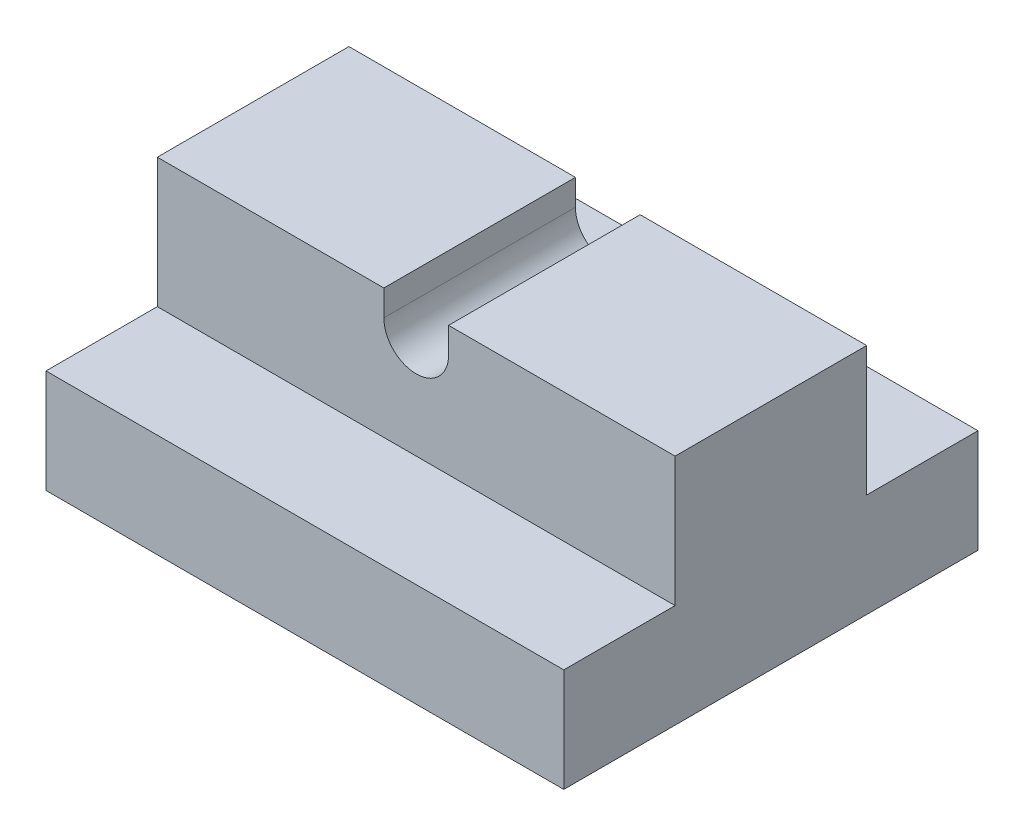
SolidWorks part; units mm, degrees
ref_plane "Front Plane" through (0, 0, 0) normal (0, 0, 1) x (1, 0, 0)
ref_plane "Top Plane" through (0, 0, 0) normal (0, 1, 0) x (1, 0, 0)
ref_plane "Right Plane" through (0, 0, 0) normal (1, 0, 0) x (0, 0, -1)
sketch "Sketch1" plane through (0, 0, 0) normal (0, 1, 0) x (1, 0, 0)
  line L1 (-5, -4) -> (5, -4)
  line L2 (-5, -4) -> (-5, 4)
  line L3 (-5, 4) -> (5, 4)
  line L4 (5, -4) -> (5, 4)
  line L5 (-5, -4) -> (5, 4) construction
  line L6 (-5, 4) -> (5, -4) construction
  point P0 (0, 0)
  dimension "D1" = 10
  dimension "D2" = 8
extrude "Boss-Extrude1" add sketch "Sketch1" along normal blind 2
sketch "Sketch2" plane through (0, 2, 0) normal (0, 1, 0) x (1, 0, 0)
  line L6 (5, -4) -> (5, 4) construction
  line L7 (-5, -1.85) -> (5, -1.85)
  line L8 (-5, -1.85) -> (-5, 1.85)
  line L9 (-5, 1.85) -> (5, 1.85)
  line L10 (5, -1.85) -> (5, 1.85)
  line L11 (-5, -1.85) -> (5, 1.85) construction
  line L12 (-5, 1.85) -> (5, -1.85) construction
  point P0 (0, 0)
  dimension "D1" = 3.7
extrude "Boss-Extrude2" add sketch "Sketch2" along normal blind 2.5
sketch "Sketch3" plane through (0, 0, 1.85) normal (0, 0, 1) x (1, 0, 0)
  line L0 (-5, 2) -> (5, 2) construction
  line L1 (-0.625, 4) -> (-0.625, 4.5)
  line L2 (-5, 4.5) -> (5, 4.5) construction
  line L3 (-0.625, 4.5) -> (0.625, 4.5)
  line L4 (0.625, 4.5) -> (0.625, 4)
  arc A0 (-0.625, 4) -> (0.625, 4) centre (0, 4) ccw
  dimension "D1" = 1.25
  dimension "D2" = 2
extrude "Cut-Extrude1" cut sketch "Sketch3" against normal up to next
equation "\"WIREDIA\"= 1.25mm"
equation "\"D1@Sketch3\"=\"WIREDIA\""
